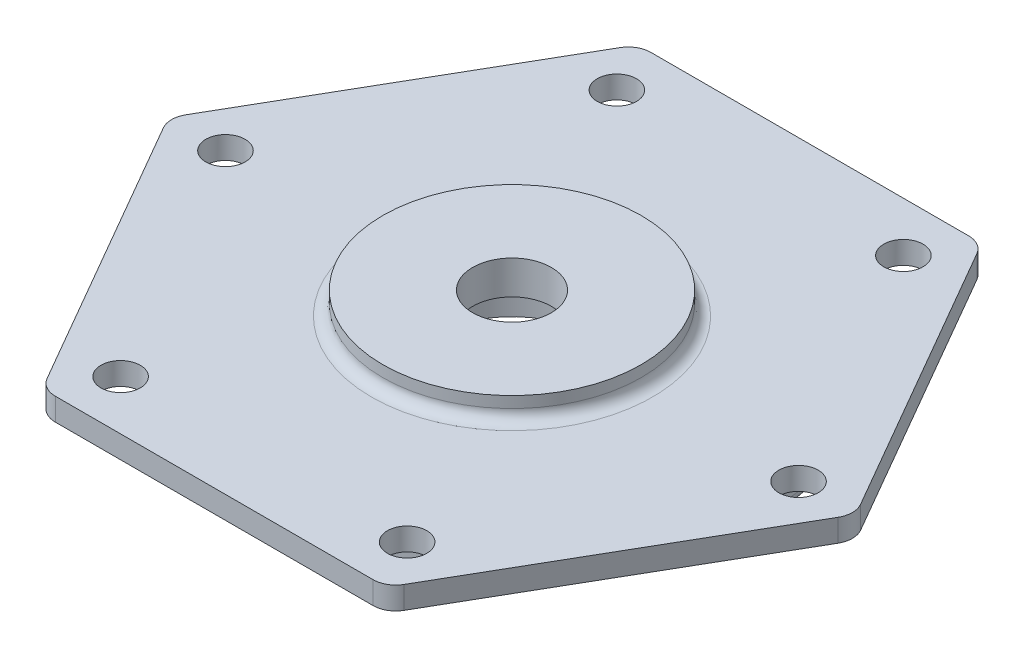
SolidWorks part; units mm, degrees
ref_plane "Front Plane" through (0, 0, 0) normal (0, 0, 1) x (1, 0, 0)
ref_plane "Top Plane" through (0, 0, 0) normal (0, 1, 0) x (1, 0, 0)
ref_plane "Right Plane" through (0, 0, 0) normal (1, 0, 0) x (0, 0, -1)
sketch "Sketch1" plane through (0, 0, 0) normal (0, 1, 0) x (1, 0, 0)
  line L1 (60.0444, 2) -> (31.7543, 51)
  line L2 (28.2902, 53) -> (-28.2902, 53)
  line L3 (-31.7543, 51) -> (-60.0444, 2)
  line L4 (-60.0444, -2) -> (-31.7543, -51)
  line L5 (-28.2902, -53) -> (28.2902, -53)
  line L6 (31.7543, -51) -> (60.0444, -2)
  circle A0 centre (0, 0) radius 53 construction
  arc A1 (-60.0444, -2) -> (-60.0444, 2) centre (-56.5803, 0) cw
  arc A2 (-31.7543, -51) -> (-28.2902, -53) centre (-28.2902, -49) ccw
  arc A3 (28.2902, -53) -> (31.7543, -51) centre (28.2902, -49) ccw
  arc A4 (60.0444, -2) -> (60.0444, 2) centre (56.5803, 0) ccw
  arc A5 (28.2902, 53) -> (31.7543, 51) centre (28.2902, 49) cw
  arc A6 (-28.2902, 53) -> (-31.7543, 51) centre (-28.2902, 49) ccw
  point P19 (61.1991, 0)
  dimension "D1" = 106
  dimension "D2" = 4
extrude "Boss-Extrude1" add sketch "Sketch1" along normal blind 4
sketch "Sketch2" plane through (0, 4, 0) normal (0, 1, 0) x (1, 0, 0)
  circle A0 centre (0, 0) radius 23
  dimension "D1" = 46
extrude "Boss-Extrude2" add sketch "Sketch2" along normal blind 4
sketch "Sketch3" plane through (0, 0, 0) normal (0, -1, 0) x (1, 0, 0)
  circle A0 centre (0, 0) radius 45
  dimension "D1" = 90
extrude "Boss-Extrude3" add sketch "Sketch3" along normal blind 6
sketch "Sketch4" plane through (0, -6, 0) normal (0, -1, 0) x (1, 0, 0)
  circle A0 centre (0, 0) radius 40
  circle A1 centre (0, 0) radius 19
  dimension "D1" = 80
  dimension "D2" = 38
extrude "Cut-Extrude1" cut sketch "Sketch4" against normal blind 6
sketch "Sketch5" plane through (0, -6, 0) normal (0, -1, 0) x (1, 0, 0)
  circle A0 centre (0, 0) radius 14
  dimension "D1" = 28
extrude "Cut-Extrude2" cut sketch "Sketch5" against normal blind 8
sketch "Sketch6" plane through (0, 2, 0) normal (0, -1, 0) x (1, 0, 0)
  circle A0 centre (0, 0) radius 7
  dimension "D1" = 14
extrude "Cut-Extrude3" cut sketch "Sketch6" against normal through all
fillet "Fillet1" radius 2 3 edges at (0, 4, 23) (0, -6, -19) (0, -6, -45)
sketch "Sketch7" plane through (0, 4, 0) normal (0, 1, 0) x (1, 0, 0)
  circle A0 centre (0, 0) radius 51 construction
  circle A1 centre (51, 0) radius 3.5
  circle A2 centre (25.5, -44.1673) radius 3.5
  circle A3 centre (-25.5, -44.1673) radius 3.5
  circle A4 centre (-51, 0) radius 3.5
  circle A5 centre (-25.5, 44.1673) radius 3.5
  circle A6 centre (25.5, 44.1673) radius 3.5
  point P18 (0, 0)
  dimension "D1" = 102
  dimension "D2" = 7
  dimension "D3" = 6
extrude "Cut-Extrude4" cut sketch "Sketch7" against normal through all
